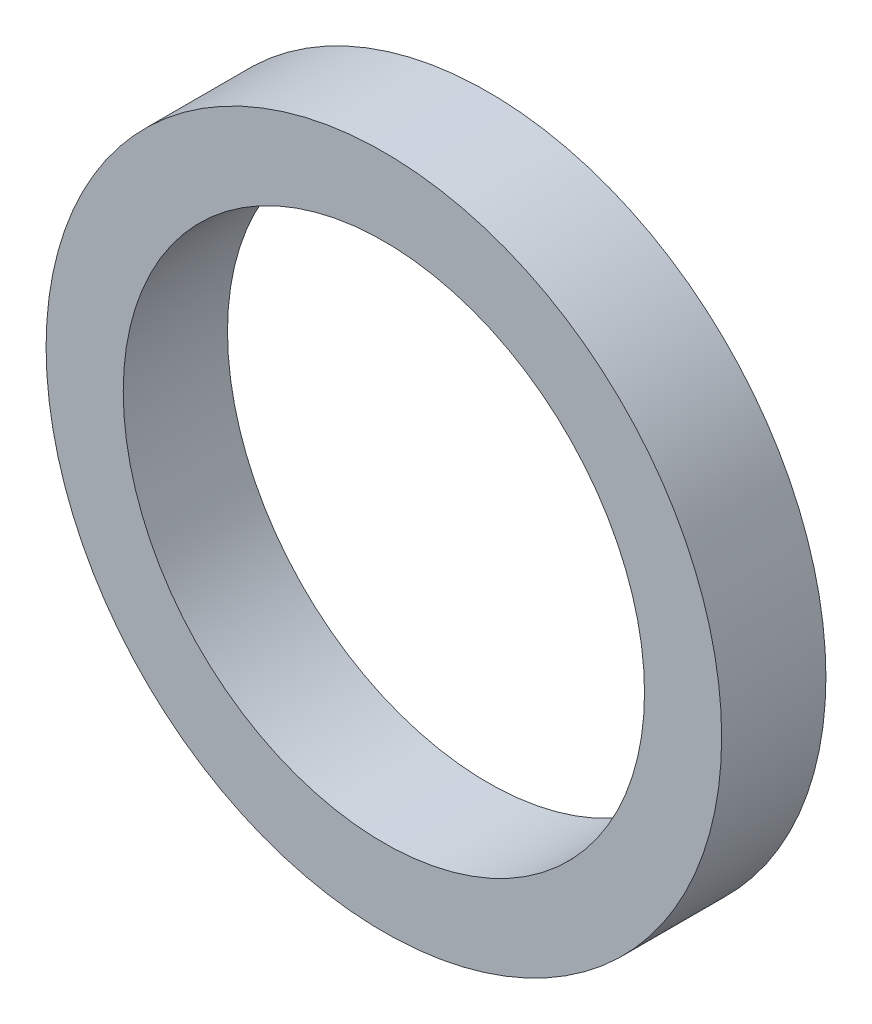
SolidWorks part; units mm, degrees
material "7075-T6 (SN)"
ref_plane "Front Plane" through (0, 0, 0) normal (0, 0, 1) x (1, 0, 0)
ref_plane "Top Plane" through (0, 0, 0) normal (0, 1, 0) x (1, 0, 0)
ref_plane "Right Plane" through (0, 0, 0) normal (1, 0, 0) x (0, 0, -1)
sketch "Sketch1" plane through (0, 0, 0) normal (0, 0, 1) x (1, 0, 0)
  circle A0 centre (0, 0) radius 6.48
  circle A1 centre (0, 0) radius 5
  dimension "D1" = 12.96
  dimension "D2" = 10
extrude "Boss-Extrude1" add sketch "Sketch1" along normal blind 2
